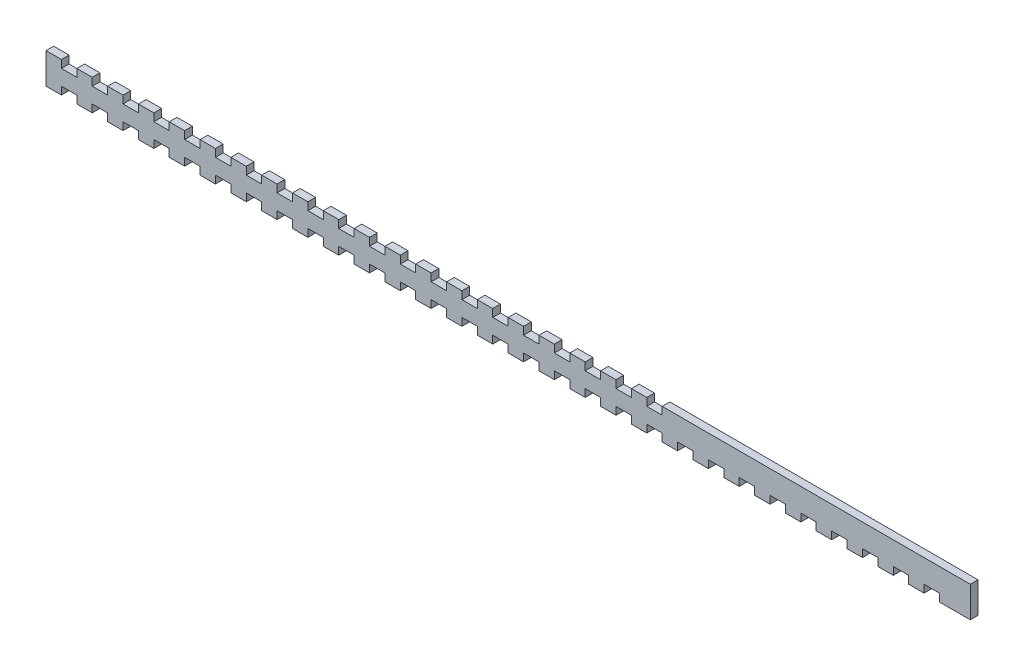
SolidWorks part; units mm, degrees
ref_plane "Plan de face" through (0, 0, 0) normal (0, 0, 1) x (1, 0, 0)
ref_plane "Plan de dessus" through (0, 0, 0) normal (0, 1, 0) x (1, 0, 0)
ref_plane "Plan de droite" through (0, 0, 0) normal (1, 0, 0) x (0, 0, -1)
sketch "Esquisse1" plane through (0, 0, 0) normal (0, 0, 1) x (1, 0, 0)
  line L0 (-300, 10) -> (200, 10)
  line L1 (-300, -10) -> (300, -10)
  line L2 (-300, -10) -> (-300, 10)
  line L4 (300, -10) -> (300, 10)
  line L5 (-300, -10) -> (300, 10) construction
  line L6 (-300, 10) -> (300, -10) construction
  line L11 (200, 10) -> (300, 10)
  point P0 (0, 0)
  dimension "D1" = 20
  dimension "D2" = 600
extrude "Boss.-Extru.1" add sketch "Esquisse1" along normal blind 5
sketch "Esquisse3" plane through (0, 0, 5) normal (0, 0, 1) x (1, 0, 0)
  line L0 (-300, -10) -> (300, -10) construction
  line L1 (-290, -10) -> (-280, -10)
  line L2 (-290, -10) -> (-290, -5)
  line L3 (-290, -5) -> (-280, -5)
  line L4 (-280, -10) -> (-280, -5)
  line L5 (-300, 10) -> (-300, -10) construction
  line L6 (-270, -10) -> (-270, -5)
  line L7 (-270, -10) -> (-260, -10)
  line L8 (-260, -10) -> (-260, -5)
  line L9 (-270, -5) -> (-260, -5)
  line L10 (-250, -10) -> (-250, -5)
  line L11 (-250, -10) -> (-240, -10)
  line L12 (-240, -10) -> (-240, -5)
  line L13 (-250, -5) -> (-240, -5)
  line L14 (-230, -10) -> (-230, -5)
  line L15 (-230, -10) -> (-220, -10)
  line L16 (-220, -10) -> (-220, -5)
  line L17 (-230, -5) -> (-220, -5)
  line L18 (-210, -10) -> (-210, -5)
  line L19 (-210, -10) -> (-200, -10)
  line L20 (-200, -10) -> (-200, -5)
  line L21 (-210, -5) -> (-200, -5)
  line L22 (-190, -10) -> (-190, -5)
  line L23 (-190, -10) -> (-180, -10)
  line L24 (-180, -10) -> (-180, -5)
  line L25 (-190, -5) -> (-180, -5)
  line L26 (-170, -10) -> (-170, -5)
  line L27 (-170, -10) -> (-160, -10)
  line L28 (-160, -10) -> (-160, -5)
  line L29 (-170, -5) -> (-160, -5)
  line L30 (-150, -10) -> (-150, -5)
  line L31 (-150, -10) -> (-140, -10)
  line L32 (-140, -10) -> (-140, -5)
  line L33 (-150, -5) -> (-140, -5)
  line L34 (-130, -10) -> (-130, -5)
  line L35 (-130, -10) -> (-120, -10)
  line L36 (-120, -10) -> (-120, -5)
  line L37 (-130, -5) -> (-120, -5)
  line L38 (-110, -10) -> (-110, -5)
  line L39 (-110, -10) -> (-100, -10)
  line L40 (-100, -10) -> (-100, -5)
  line L41 (-110, -5) -> (-100, -5)
  line L42 (-90, -10) -> (-90, -5)
  line L43 (-90, -10) -> (-80, -10)
  line L44 (-80, -10) -> (-80, -5)
  line L45 (-90, -5) -> (-80, -5)
  line L46 (-70, -10) -> (-70, -5)
  line L47 (-70, -10) -> (-60, -10)
  line L48 (-60, -10) -> (-60, -5)
  line L49 (-70, -5) -> (-60, -5)
  line L50 (-50, -10) -> (-50, -5)
  line L51 (-50, -10) -> (-40, -10)
  line L52 (-40, -10) -> (-40, -5)
  line L53 (-50, -5) -> (-40, -5)
  line L54 (-30, -10) -> (-30, -5)
  line L55 (-30, -10) -> (-20, -10)
  line L56 (-20, -10) -> (-20, -5)
  line L57 (-30, -5) -> (-20, -5)
  line L58 (-10, -10) -> (-10, -5)
  line L59 (-10, -10) -> (0, -10)
  line L60 (0, -10) -> (0, -5)
  line L61 (-10, -5) -> (0, -5)
  line L62 (10, -10) -> (10, -5)
  line L63 (10, -10) -> (20, -10)
  line L64 (20, -10) -> (20, -5)
  line L65 (10, -5) -> (20, -5)
  line L66 (30, -10) -> (30, -5)
  line L67 (30, -10) -> (40, -10)
  line L68 (40, -10) -> (40, -5)
  line L69 (30, -5) -> (40, -5)
  line L70 (50, -10) -> (50, -5)
  line L71 (50, -10) -> (60, -10)
  line L72 (60, -10) -> (60, -5)
  line L73 (50, -5) -> (60, -5)
  line L74 (70, -10) -> (70, -5)
  line L75 (70, -10) -> (80, -10)
  line L76 (80, -10) -> (80, -5)
  line L77 (70, -5) -> (80, -5)
  line L78 (90, -10) -> (90, -5)
  line L79 (90, -10) -> (100, -10)
  line L80 (100, -10) -> (100, -5)
  line L81 (90, -5) -> (100, -5)
  line L82 (110, -10) -> (110, -5)
  line L83 (110, -10) -> (120, -10)
  line L84 (120, -10) -> (120, -5)
  line L85 (110, -5) -> (120, -5)
  line L86 (130, -10) -> (130, -5)
  line L87 (130, -10) -> (140, -10)
  line L88 (140, -10) -> (140, -5)
  line L89 (130, -5) -> (140, -5)
  line L90 (150, -10) -> (150, -5)
  line L91 (150, -10) -> (160, -10)
  line L92 (160, -10) -> (160, -5)
  line L93 (150, -5) -> (160, -5)
  line L94 (170, -10) -> (170, -5)
  line L95 (170, -10) -> (180, -10)
  line L96 (180, -10) -> (180, -5)
  line L97 (170, -5) -> (180, -5)
  line L98 (190, -10) -> (190, -5)
  line L99 (190, -10) -> (200, -10)
  line L100 (200, -10) -> (200, -5)
  line L101 (190, -5) -> (200, -5)
  line L102 (210, -10) -> (210, -5)
  line L103 (210, -10) -> (220, -10)
  line L104 (220, -10) -> (220, -5)
  line L105 (210, -5) -> (220, -5)
  line L106 (230, -10) -> (230, -5)
  line L107 (230, -10) -> (240, -10)
  line L108 (240, -10) -> (240, -5)
  line L109 (230, -5) -> (240, -5)
  line L110 (250, -10) -> (250, -5)
  line L111 (250, -10) -> (260, -10)
  line L112 (260, -10) -> (260, -5)
  line L113 (250, -5) -> (260, -5)
  line L114 (270, -10) -> (270, -5)
  line L115 (270, -10) -> (280, -10)
  line L116 (280, -10) -> (280, -5)
  line L117 (270, -5) -> (280, -5)
  line L118 (300, 10) -> (-300, 10) construction
  line L119 (-290, 10) -> (-280, 10)
  line L120 (-290, 10) -> (-290, 5)
  line L121 (-290, 5) -> (-280, 5)
  line L122 (-280, 10) -> (-280, 5)
  line L123 (-270, 10) -> (-270, 5)
  line L124 (-270, 10) -> (-260, 10)
  line L125 (-260, 10) -> (-260, 5)
  line L126 (-270, 5) -> (-260, 5)
  line L127 (-250, 10) -> (-250, 5)
  line L128 (-250, 10) -> (-240, 10)
  line L129 (-240, 10) -> (-240, 5)
  line L130 (-250, 5) -> (-240, 5)
  line L131 (-230, 10) -> (-230, 5)
  line L132 (-230, 10) -> (-220, 10)
  line L133 (-220, 10) -> (-220, 5)
  line L134 (-230, 5) -> (-220, 5)
  line L135 (-210, 10) -> (-210, 5)
  line L136 (-210, 10) -> (-200, 10)
  line L137 (-200, 10) -> (-200, 5)
  line L138 (-210, 5) -> (-200, 5)
  line L139 (-190, 10) -> (-190, 5)
  line L140 (-190, 10) -> (-180, 10)
  line L141 (-180, 10) -> (-180, 5)
  line L142 (-190, 5) -> (-180, 5)
  line L143 (-170, 10) -> (-170, 5)
  line L144 (-170, 10) -> (-160, 10)
  line L145 (-160, 10) -> (-160, 5)
  line L146 (-170, 5) -> (-160, 5)
  line L147 (-150, 10) -> (-150, 5)
  line L148 (-150, 10) -> (-140, 10)
  line L149 (-140, 10) -> (-140, 5)
  line L150 (-150, 5) -> (-140, 5)
  line L151 (-130, 10) -> (-130, 5)
  line L152 (-130, 10) -> (-120, 10)
  line L153 (-120, 10) -> (-120, 5)
  line L154 (-130, 5) -> (-120, 5)
  line L155 (-110, 10) -> (-110, 5)
  line L156 (-110, 10) -> (-100, 10)
  line L157 (-100, 10) -> (-100, 5)
  line L158 (-110, 5) -> (-100, 5)
  line L159 (-90, 10) -> (-90, 5)
  line L160 (-90, 10) -> (-80, 10)
  line L161 (-80, 10) -> (-80, 5)
  line L162 (-90, 5) -> (-80, 5)
  line L163 (-70, 10) -> (-70, 5)
  line L164 (-70, 10) -> (-60, 10)
  line L165 (-60, 10) -> (-60, 5)
  line L166 (-70, 5) -> (-60, 5)
  line L167 (-50, 10) -> (-50, 5)
  line L168 (-50, 10) -> (-40, 10)
  line L169 (-40, 10) -> (-40, 5)
  line L170 (-50, 5) -> (-40, 5)
  line L171 (-30, 10) -> (-30, 5)
  line L172 (-30, 10) -> (-20, 10)
  line L173 (-20, 10) -> (-20, 5)
  line L174 (-30, 5) -> (-20, 5)
  line L175 (-10, 10) -> (-10, 5)
  line L176 (-10, 10) -> (0, 10)
  line L177 (0, 10) -> (0, 5)
  line L178 (-10, 5) -> (0, 5)
  line L179 (10, 10) -> (10, 5)
  line L180 (10, 10) -> (20, 10)
  line L181 (20, 10) -> (20, 5)
  line L182 (10, 5) -> (20, 5)
  line L183 (30, 10) -> (30, 5)
  line L184 (30, 10) -> (40, 10)
  line L185 (40, 10) -> (40, 5)
  line L186 (30, 5) -> (40, 5)
  line L187 (50, 10) -> (50, 5)
  line L188 (50, 10) -> (60, 10)
  line L189 (60, 10) -> (60, 5)
  line L190 (50, 5) -> (60, 5)
  line L191 (70, 10) -> (70, 5)
  line L192 (70, 10) -> (80, 10)
  line L193 (80, 10) -> (80, 5)
  line L194 (70, 5) -> (80, 5)
  line L195 (90, 10) -> (90, 5)
  line L196 (90, 10) -> (100, 10)
  line L197 (100, 10) -> (100, 5)
  line L198 (90, 5) -> (100, 5)
  dimension "D1" = 10
  dimension "D2" = 5
  dimension "D3" = 10
  dimension "D5" = 5
  dimension "D6" = 10
  dimension "D7" = 10
  dimension "D4" = 29
  dimension "D8" = 20
extrude "Enlèv. mat.-Extru.1" cut sketch "Esquisse3" against normal through all
